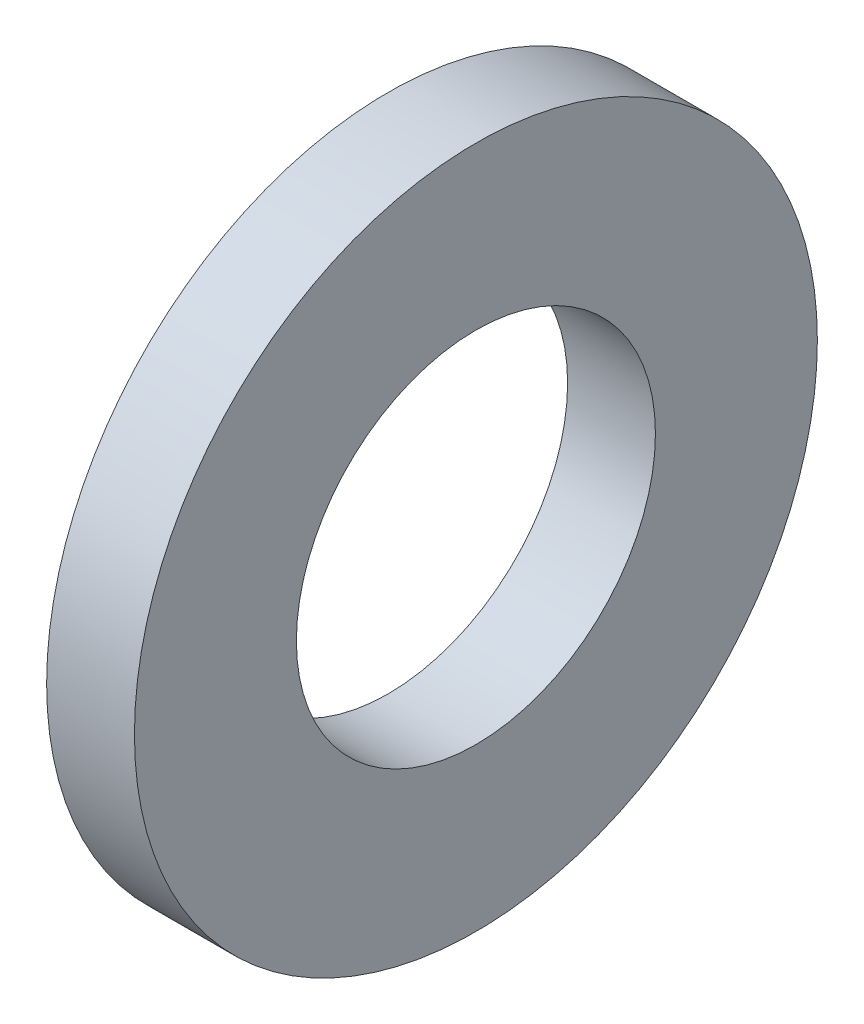
SolidWorks part; units mm, degrees
ref_plane "Plane1" through (0, 0, 0) normal (0, 0, 1) x (1, 0, 0)
ref_plane "Plane2" through (0, 0, 0) normal (0, 1, 0) x (1, 0, 0)
ref_plane "Plane3" through (0, 0, 0) normal (1, 0, 0) x (0, 0, -1)
other "Configuration Table"
sketch "Sketch1" plane through (0, 0, 0) normal (0, 0, 1) x (1, 0, 0)
  line L0 (-34.925, 0) -> (9.525, 0) construction
  line L1 (0, 1.84) -> (0, 3.5)
  line L2 (0, 3.5) -> (-0.9, 3.5)
  line L3 (-0.9, 3.5) -> (-0.9, 1.84)
  line L4 (-0.9, 1.84) -> (0, 1.84)
  dimension "Thickness" = 0.9
  dimension "Inside_dia" = 3.68
  dimension "Outside_dia" = 7
revolve "Base-Revolve" add sketch "Sketch1" angle 360 about L0
